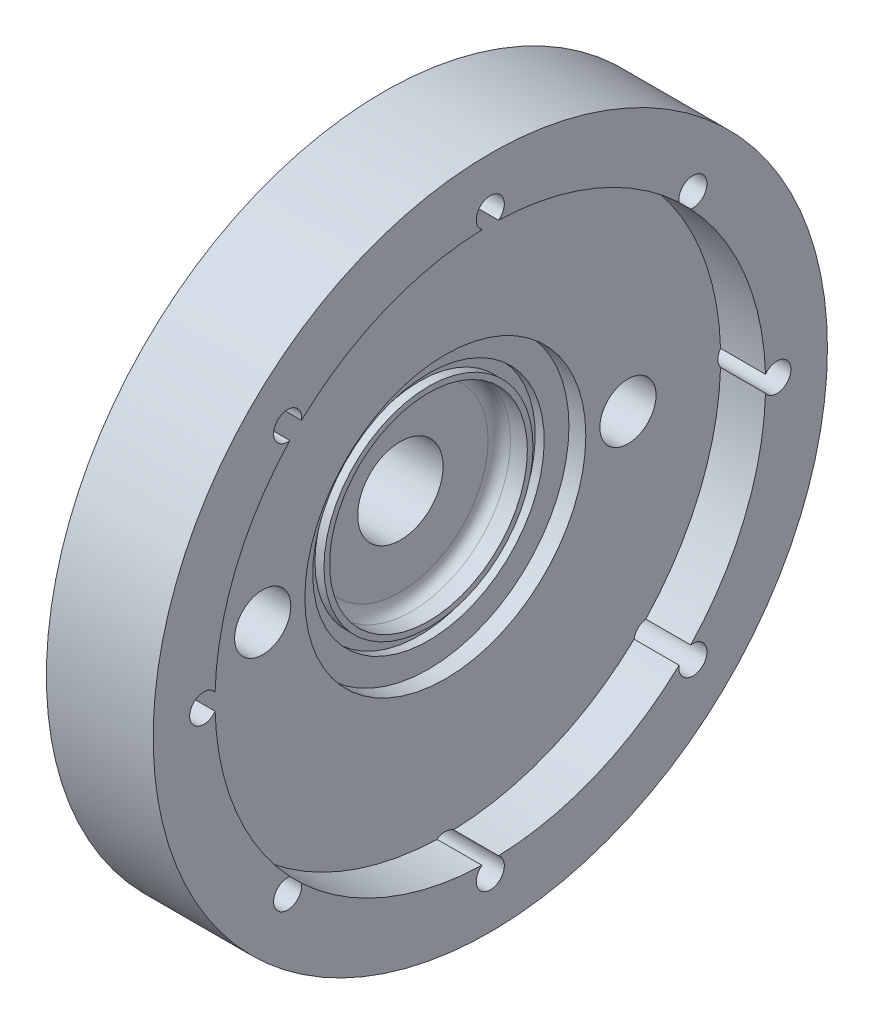
SolidWorks part; units mm, degrees
ref_plane "Front Plane" through (0, 0, 0) normal (0, 0, 1) x (1, 0, 0)
ref_plane "Top Plane" through (0, 0, 0) normal (0, 1, 0) x (1, 0, 0)
ref_plane "Right Plane" through (0, 0, 0) normal (1, 0, 0) x (0, 0, -1)
sketch "Sketch1" plane through (0, 0, 0) normal (0, 0, 1) x (1, 0, 0)
  line L1 (0, 76.2) -> (-10.16, 76.2)
  line L2 (-10.16, 76.2) -> (-10.16, 21.082)
  line L3 (-15.24, 16.002) -> (-31.75, 16.002)
  line L4 (-31.75, 16.002) -> (-31.75, 9.652)
  line L5 (-31.75, 9.652) -> (-6.35, 9.652)
  line L6 (-6.35, 9.652) -> (-6.35, 19.812)
  line L7 (-3.81, 22.352) -> (0, 22.352)
  line L8 (0, 22.352) -> (0, 76.2)
  line L9 (0, 0) -> (-31.75, 0) construction
  line L10 (-31.75, 0) -> (-31.75, 9.652) construction
  arc A0 (-10.16, 21.082) -> (-15.24, 16.002) centre (-15.24, 21.082) cw
  arc A2 (-6.35, 19.812) -> (-3.81, 22.352) centre (-3.81, 19.812) cw
  dimension "Top Part Outer Fillet" = 5.08
  dimension "LOX Manifold Fillet" = 2.54
  dimension "LOX Valve Thickness" = 6.35
  dimension "Distance between Manifold and Outer Surface" = 3.81
  dimension "LOX Valve Radius" = 9.652
  dimension "Depth of LOX Manifold" = 6.35
  dimension "Valve Entry Depth" = 25.4
  dimension "Comp Radius" = 76.2
  dimension "Manifold Radius" = 22.352
revolve "Revolve1" add sketch "Sketch1" angle 360 about L9
sketch "Sketch4" plane through (0, 0, 0) normal (0, 0, 1) x (1, 0, 0)
  line L0 (0, -76.2) -> (0, 76.2) construction
  line L1 (0, 23.622) -> (-2.032, 23.622)
  line L2 (0, 23.622) -> (0, 26.162)
  line L3 (0, 26.162) -> (-2.032, 26.162)
  line L4 (-2.032, 23.622) -> (-2.032, 26.162)
  line L5 (0, 0) -> (-31.75, 0) construction
  line L6 (-31.75, 16.002) -> (-31.75, -16.002) construction
  dimension "Top ORing Width" = 2.54
  dimension "Top ORing Depth" = 2.032
  dimension "Top ORing Radius" = 23.622
revolve "Cut-Revolve1" cut sketch "Sketch4" angle 360 about L5
sketch "Sketch5" plane through (0, 0, 0) normal (1, 0, 0) x (0, 0, -1)
  circle A0 centre (0, 0) radius 31.75
  circle A1 centre (0, 0) radius 76.2
extrude "Boss-Extrude1" add sketch "Sketch5" along normal blind 3.81
sketch "Sketch6" plane through (3.81, 0, 0) normal (1, 0, 0) x (0, 0, -1)
  circle A0 centre (0, 0) radius 62.23
  circle A1 centre (0, 0) radius 76.2
extrude "Boss-Extrude2" add sketch "Sketch6" along normal blind 10.16
sketch "Sketch2" plane through (0, 0, 0) normal (1, 0, 0) x (0, 0, -1)
  line L0 (-41.275, 0) -> (41.275, 0) construction
  circle A0 centre (41.275, 0) radius 6.35
  circle A1 centre (-41.275, 0) radius 6.35
  point P8 (0, 0)
  dimension "Valve Diameter" = 12.7
  dimension "Distance of Prop Valves" = 82.55
extrude "Cut-Extrude1" cut sketch "Sketch2" against normal through all and the other way through all
sketch "Sketch3" plane through (0, 0, 0) normal (1, 0, 0) x (0, 0, -1)
  line L0 (0, 0) -> (64.77, 0) construction
  circle A0 centre (64.77, 0) radius 3.175
  dimension "D1" = 64.77
  dimension "Screw Hole Diameter" = 6.35
extrude "Cut-Extrude2" cut sketch "Sketch3" against normal through all both and the other way through all
pattern_circular "CirPattern1" count 8 over 360 about axis through (0, 0, 0) along (1, 0, 0) of "Cut-Extrude2"
